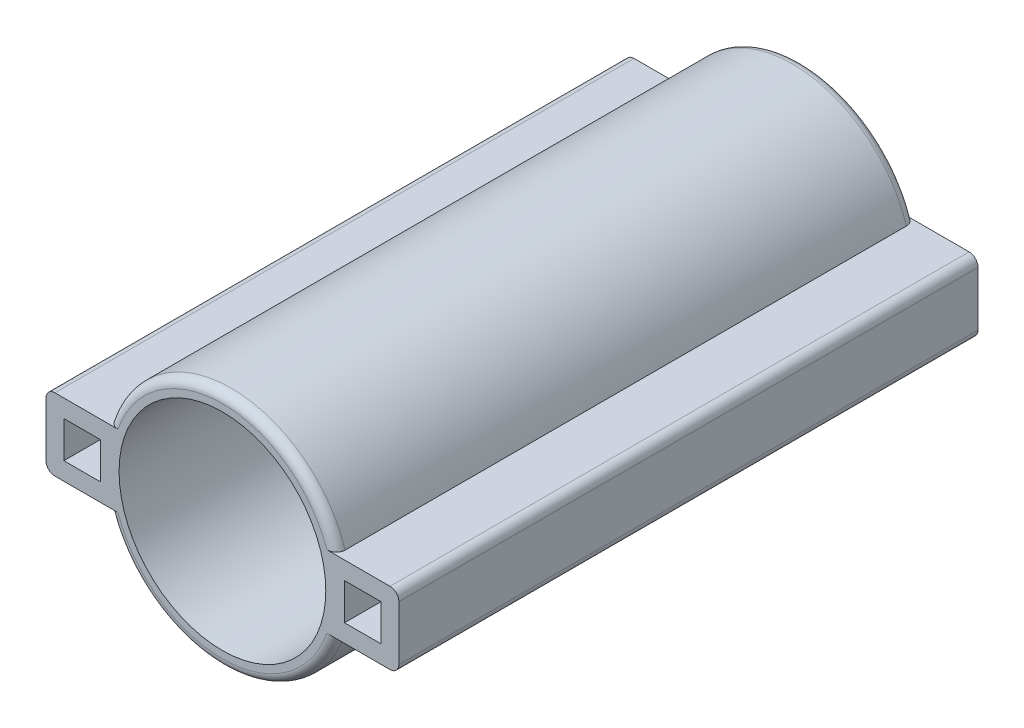
SolidWorks part; units mm, degrees
ref_plane "Front Plane" through (0, 0, 0) normal (0, 0, 1) x (1, 0, 0)
ref_plane "Top Plane" through (0, 0, 0) normal (0, 1, 0) x (1, 0, 0)
ref_plane "Right Plane" through (0, 0, 0) normal (1, 0, 0) x (0, 0, -1)
sketch "Sketch1" plane through (0, 0, 0) normal (0, 0, 1) x (1, 0, 0)
  line L0 (-68.5, -1.0833) -> (-68.5, 10.25)
  line L1 (-68.5, 10.25) -> (-89, 10.25)
  line L2 (-89, 10.25) -> (-89, -10.25)
  line L3 (-89, -10.25) -> (-68.5, -10.25)
  line L4 (-68.5, -10.25) -> (-68.5, -1.0833)
  line L5 (0, -55) -> (0, 55) construction
  line L6 (-99, -20.25) -> (-58.5, -20.25)
  line L7 (-99, -20.25) -> (-99, 20.25)
  line L8 (-99, 20.25) -> (-58.5, 20.25)
  line L9 (-58.5, -20.25) -> (-58.5, 20.25)
  line L10 (-99, -20.25) -> (-58.5, 20.25) construction
  line L11 (-99, 20.25) -> (-58.5, -20.25) construction
  line L12 (99, 20.25) -> (58.5, 20.25)
  line L13 (68.5, 10.25) -> (89, 10.25)
  line L14 (68.5, -1.0833) -> (68.5, 10.25)
  line L15 (68.5, -10.25) -> (68.5, -1.0833)
  line L16 (58.5, -20.25) -> (58.5, 20.25)
  line L17 (99, -20.25) -> (58.5, -20.25)
  line L18 (89, -10.25) -> (68.5, -10.25)
  line L19 (99, -20.25) -> (99, 20.25)
  line L20 (89, 10.25) -> (89, -10.25)
  circle A0 centre (0, 0) radius 58
  circle A1 centre (0, 0) radius 67
  point P6 (-78.75, 0)
  dimension "D1" = 9
  dimension "D2" = 116
  dimension "D6" = 10
  dimension "D3" = 68.5
  dimension "D4" = 20.5
  dimension "D5" = 20.5
  dimension "D7" = 10
  dimension "D8" = 10
  dimension "D9" = 10
  dimension "D10" = 10.25
extrude "Boss-Extrude6" add sketch "Sketch1" along normal blind 325 contours L12 A1 L8 L9 L6 L17 L16 A0 | L8 A1 L1 L0 L4 L3 L6 L9 | A1 L8 L7 L6 L3 L2 L1 | L13 A1 L12 L16 L17 L18 L15 L14 | A1 L13 L20 L18 L17 L19 L12
fillet "Fillet4" radius 5 8 edges at (0, 67, 0) (0, 67, 325) (0, -67, 0) (0, -67, 325) (99, -20.25, 162.5) (99, 20.25, 162.5) (-99, -20.25, 162.5) (-99, 20.25, 162.5)
